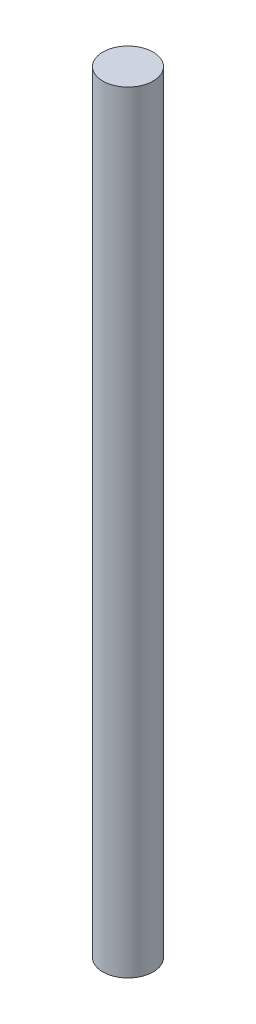
SolidWorks part; units mm, degrees
ref_plane "前视基准面" through (0, 0, 0) normal (0, 0, 1) x (1, 0, 0)
ref_plane "上视基准面" through (0, 0, 0) normal (0, 1, 0) x (1, 0, 0)
ref_plane "右视基准面" through (0, 0, 0) normal (1, 0, 0) x (0, 0, -1)
sketch "草图1" plane through (0, 0, 0) normal (0, 1, 0) x (1, 0, 0)
  circle A0 centre (0, 0) radius 1.5
  dimension "D1" = 3
extrude "凸台-拉伸1" add sketch "草图1" along normal blind 46
